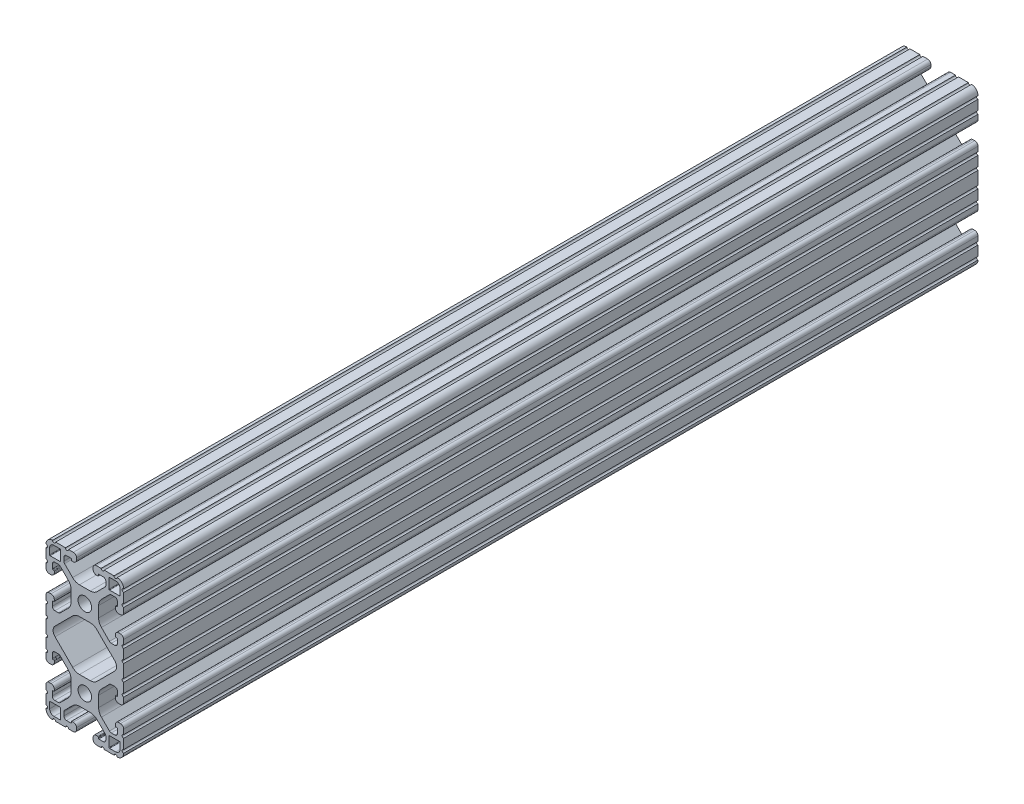
SolidWorks part; units mm, degrees
ref_plane "Front Plane" through (0, 0, 0) normal (0, 0, 1) x (1, 0, 0)
ref_plane "Top Plane" through (0, 0, 0) normal (0, 1, 0) x (1, 0, 0)
ref_plane "Right Plane" through (0, 0, 0) normal (1, 0, 0) x (0, 0, -1)
ref_plane "Plane1" through (0, 0, -914.4) normal (0, 0, -1) x (-1, 0, 0)
sketch "Sketch1" plane through (0, 0, -914.4) normal (0, 0, -1) x (-1, 0, 0)
  line L0 (19.05, -14.3256) -> (19.05, -9.4996)
  line L1 (19.05, -7.9756) -> (19.05, -5.6388)
  line L2 (17.4752, -4.064) -> (16.5608, -4.064)
  line L3 (14.986, -5.6388) -> (14.986, -6.35)
  line L4 (15.24, -6.604) -> (15.7099, -6.604)
  line L5 (15.9639, -6.858) -> (15.9639, -9.017)
  line L6 (14.6939, -10.287) -> (12.9683, -10.287)
  line L7 (12.0703, -9.915) -> (8.1476, -5.9923)
  line L8 (6.7564, -2.6337) -> (6.7564, 2.6337)
  line L9 (8.1476, 5.9923) -> (12.0703, 9.915)
  line L10 (12.9683, 10.287) -> (14.6939, 10.287)
  line L11 (15.9639, 9.017) -> (15.9639, 6.858)
  line L12 (15.7099, 6.604) -> (15.24, 6.604)
  line L13 (14.986, 6.35) -> (14.986, 5.6388)
  line L14 (16.5608, 4.064) -> (17.4752, 4.064)
  line L15 (19.05, 5.6388) -> (19.05, 7.9756)
  line L16 (19.05, 9.4996) -> (19.05, 14.3256)
  line L17 (19.05, 15.8496) -> (19.05, 22.2504)
  line L18 (19.05, 23.7744) -> (19.05, 28.6004)
  line L19 (19.05, 30.1244) -> (19.05, 32.4612)
  line L20 (17.4752, 34.036) -> (16.5608, 34.036)
  line L21 (14.986, 32.4612) -> (14.986, 31.75)
  line L22 (15.24, 31.496) -> (15.7099, 31.496)
  line L23 (15.9639, 31.242) -> (15.9639, 29.083)
  line L24 (14.6939, 27.813) -> (12.9683, 27.813)
  line L25 (12.0703, 28.185) -> (8.1476, 32.1077)
  line L26 (6.7564, 35.4663) -> (6.7564, 40.7337)
  line L27 (8.1476, 44.0923) -> (12.0703, 48.015)
  line L28 (12.9683, 48.387) -> (14.6939, 48.387)
  line L29 (15.9639, 47.117) -> (15.9639, 44.958)
  line L30 (15.7099, 44.704) -> (15.24, 44.704)
  line L31 (14.986, 44.45) -> (14.986, 43.7388)
  line L32 (16.5608, 42.164) -> (17.4752, 42.164)
  line L33 (19.05, 43.7388) -> (19.05, 46.0756)
  line L34 (19.05, 47.5996) -> (19.05, 52.4256)
  line L35 (14.3256, 57.15) -> (9.4996, 57.15)
  line L36 (7.9756, 57.15) -> (5.6388, 57.15)
  line L37 (4.064, 55.5752) -> (4.064, 54.6608)
  line L38 (5.6388, 53.086) -> (6.35, 53.086)
  line L39 (6.604, 53.34) -> (6.604, 53.8099)
  line L40 (6.858, 54.0639) -> (9.017, 54.0639)
  line L41 (10.287, 52.7939) -> (10.287, 51.0683)
  line L42 (9.915, 50.1703) -> (5.9923, 46.2476)
  line L43 (2.6337, 44.8564) -> (-2.6337, 44.8564)
  line L44 (-5.9923, 46.2476) -> (-9.915, 50.1703)
  line L45 (-10.287, 51.0683) -> (-10.287, 52.7939)
  line L46 (-9.017, 54.0639) -> (-6.858, 54.0639)
  line L47 (-6.604, 53.8099) -> (-6.604, 53.34)
  line L48 (-6.35, 53.086) -> (-5.6388, 53.086)
  line L49 (-4.064, 54.6608) -> (-4.064, 55.5752)
  line L50 (-5.6388, 57.15) -> (-7.9756, 57.15)
  line L51 (-9.4996, 57.15) -> (-14.3256, 57.15)
  line L52 (-19.05, 52.4256) -> (-19.05, 47.5996)
  line L53 (-19.05, 46.0756) -> (-19.05, 43.7388)
  line L54 (-17.4752, 42.164) -> (-16.5608, 42.164)
  line L55 (-14.986, 43.7388) -> (-14.986, 44.45)
  line L56 (-15.24, 44.704) -> (-15.7099, 44.704)
  line L57 (-15.9639, 44.958) -> (-15.9639, 47.117)
  line L58 (-14.6939, 48.387) -> (-12.9683, 48.387)
  line L59 (-12.0703, 48.015) -> (-8.1476, 44.0923)
  line L60 (-6.7564, 40.7337) -> (-6.7564, 35.4663)
  line L61 (-8.1476, 32.1077) -> (-12.0703, 28.185)
  line L62 (-12.9683, 27.813) -> (-14.6939, 27.813)
  line L63 (-15.9639, 29.083) -> (-15.9639, 31.242)
  line L64 (-15.7099, 31.496) -> (-15.24, 31.496)
  line L65 (-14.986, 31.75) -> (-14.986, 32.4612)
  line L66 (-16.5608, 34.036) -> (-17.4752, 34.036)
  line L67 (-19.05, 32.4612) -> (-19.05, 30.1244)
  line L68 (-19.05, 28.6004) -> (-19.05, 23.7744)
  line L69 (-19.05, 22.2504) -> (-19.05, 15.8496)
  line L70 (-19.05, 14.3256) -> (-19.05, 9.4996)
  line L71 (-19.05, 7.9756) -> (-19.05, 5.6388)
  line L72 (-17.4752, 4.064) -> (-16.5608, 4.064)
  line L73 (-14.986, 5.6388) -> (-14.986, 6.35)
  line L74 (-15.24, 6.604) -> (-15.7099, 6.604)
  line L75 (-15.9639, 6.858) -> (-15.9639, 9.017)
  line L76 (-14.6939, 10.287) -> (-12.9683, 10.287)
  line L77 (-12.0703, 9.915) -> (-8.1476, 5.9923)
  line L78 (-6.7564, 2.6337) -> (-6.7564, -2.6337)
  line L79 (-8.1476, -5.9923) -> (-12.0703, -9.915)
  line L80 (-12.9683, -10.287) -> (-14.6939, -10.287)
  line L81 (-15.9639, -9.017) -> (-15.9639, -6.858)
  line L82 (-15.7099, -6.604) -> (-15.24, -6.604)
  line L83 (-14.986, -6.35) -> (-14.986, -5.6388)
  line L84 (-16.5608, -4.064) -> (-17.4752, -4.064)
  line L85 (-19.05, -5.6388) -> (-19.05, -7.9756)
  line L86 (-19.05, -9.4996) -> (-19.05, -14.3256)
  line L87 (-14.3256, -19.05) -> (-9.4996, -19.05)
  line L88 (-7.9756, -19.05) -> (-5.6388, -19.05)
  line L89 (-4.064, -17.4752) -> (-4.064, -16.5608)
  line L90 (-5.6388, -14.986) -> (-6.35, -14.986)
  line L91 (-6.604, -15.24) -> (-6.604, -15.7099)
  line L92 (-6.858, -15.9639) -> (-9.017, -15.9639)
  line L93 (-10.287, -14.6939) -> (-10.287, -12.9683)
  line L94 (-9.915, -12.0703) -> (-5.9923, -8.1476)
  line L95 (-2.6337, -6.7564) -> (2.6337, -6.7564)
  line L96 (5.9923, -8.1476) -> (9.915, -12.0703)
  line L97 (10.287, -12.9683) -> (10.287, -14.6939)
  line L98 (9.017, -15.9639) -> (6.858, -15.9639)
  line L99 (6.604, -15.7099) -> (6.604, -15.24)
  line L100 (6.35, -14.986) -> (5.6388, -14.986)
  line L101 (4.064, -16.5608) -> (4.064, -17.4752)
  line L102 (5.6388, -19.05) -> (7.9756, -19.05)
  line L103 (9.4996, -19.05) -> (14.3256, -19.05)
  line L104 (-11.8872, -12.1412) -> (-11.8872, -17.018)
  line L105 (-12.1412, -17.272) -> (-15.1384, -17.272)
  line L106 (-17.272, -15.1384) -> (-17.272, -12.1412)
  line L107 (-17.018, -11.8872) -> (-12.1412, -11.8872)
  line L108 (-15.1384, 55.372) -> (-12.1412, 55.372)
  line L109 (-11.8872, 55.118) -> (-11.8872, 50.2412)
  line L110 (-12.1412, 49.9872) -> (-17.018, 49.9872)
  line L111 (-17.272, 50.2412) -> (-17.272, 53.2384)
  line L112 (5.9923, 29.9524) -> (14.6189, 21.3259)
  line L113 (14.6189, 16.7741) -> (5.9923, 8.1476)
  line L114 (2.6337, 6.7564) -> (-2.6337, 6.7564)
  line L115 (-5.9923, 8.1476) -> (-14.6189, 16.7741)
  line L116 (-14.6189, 21.3259) -> (-5.9923, 29.9524)
  line L117 (-2.6337, 31.3436) -> (2.6337, 31.3436)
  line L118 (17.272, -12.1412) -> (17.272, -15.1384)
  line L119 (15.1384, -17.272) -> (12.1412, -17.272)
  line L120 (11.8872, -17.018) -> (11.8872, -12.1412)
  line L121 (12.1412, -11.8872) -> (17.018, -11.8872)
  line L122 (12.1412, 55.372) -> (15.1384, 55.372)
  line L123 (17.272, 53.2384) -> (17.272, 50.2412)
  line L124 (17.018, 49.9872) -> (12.1412, 49.9872)
  line L125 (11.8872, 50.2412) -> (11.8872, 55.118)
  circle A0 centre (0, 0) radius 3.3274
  arc A1 (19.05, -15.8496) -> (19.05, -14.3256) centre (19.05, -15.0876) cw
  arc A2 (19.05, -9.4996) -> (19.05, -7.9756) centre (19.05, -8.7376) cw
  arc A3 (19.05, -5.6388) -> (17.4752, -4.064) centre (17.4752, -5.6388) ccw
  arc A4 (16.5608, -4.064) -> (14.986, -5.6388) centre (16.5608, -5.6388) ccw
  arc A5 (14.986, -6.35) -> (15.24, -6.604) centre (15.24, -6.35) ccw
  arc A6 (15.7099, -6.604) -> (15.9639, -6.858) centre (15.7099, -6.858) cw
  arc A7 (15.9639, -9.017) -> (14.6939, -10.287) centre (14.6939, -9.017) cw
  arc A8 (12.9683, -10.287) -> (12.0703, -9.915) centre (12.9683, -9.017) cw
  arc A9 (8.1476, -5.9923) -> (6.7564, -2.6337) centre (11.5062, -2.6337) cw
  arc A10 (6.7564, 2.6337) -> (8.1476, 5.9923) centre (11.5062, 2.6337) cw
  arc A11 (12.0703, 9.915) -> (12.9683, 10.287) centre (12.9683, 9.017) cw
  arc A12 (14.6939, 10.287) -> (15.9639, 9.017) centre (14.6939, 9.017) cw
  arc A13 (15.9639, 6.858) -> (15.7099, 6.604) centre (15.7099, 6.858) cw
  arc A14 (15.24, 6.604) -> (14.986, 6.35) centre (15.24, 6.35) ccw
  arc A15 (14.986, 5.6388) -> (16.5608, 4.064) centre (16.5608, 5.6388) ccw
  arc A16 (17.4752, 4.064) -> (19.05, 5.6388) centre (17.4752, 5.6388) ccw
  arc A17 (19.05, 7.9756) -> (19.05, 9.4996) centre (19.05, 8.7376) cw
  arc A18 (19.05, 14.3256) -> (19.05, 15.8496) centre (19.05, 15.0876) cw
  arc A19 (19.05, 22.2504) -> (19.05, 23.7744) centre (19.05, 23.0124) cw
  arc A20 (19.05, 28.6004) -> (19.05, 30.1244) centre (19.05, 29.3624) cw
  arc A21 (19.05, 32.4612) -> (17.4752, 34.036) centre (17.4752, 32.4612) ccw
  arc A22 (16.5608, 34.036) -> (14.986, 32.4612) centre (16.5608, 32.4612) ccw
  arc A23 (14.986, 31.75) -> (15.24, 31.496) centre (15.24, 31.75) ccw
  arc A24 (15.7099, 31.496) -> (15.9639, 31.242) centre (15.7099, 31.242) cw
  arc A25 (15.9639, 29.083) -> (14.6939, 27.813) centre (14.6939, 29.083) cw
  arc A26 (12.9683, 27.813) -> (12.0703, 28.185) centre (12.9683, 29.083) cw
  arc A27 (8.1476, 32.1077) -> (6.7564, 35.4663) centre (11.5062, 35.4663) cw
  arc A28 (6.7564, 40.7337) -> (8.1476, 44.0923) centre (11.5062, 40.7337) cw
  arc A29 (12.0703, 48.015) -> (12.9683, 48.387) centre (12.9683, 47.117) cw
  arc A30 (14.6939, 48.387) -> (15.9639, 47.117) centre (14.6939, 47.117) cw
  arc A31 (15.9639, 44.958) -> (15.7099, 44.704) centre (15.7099, 44.958) cw
  arc A32 (15.24, 44.704) -> (14.986, 44.45) centre (15.24, 44.45) ccw
  arc A33 (14.986, 43.7388) -> (16.5608, 42.164) centre (16.5608, 43.7388) ccw
  arc A34 (17.4752, 42.164) -> (19.05, 43.7388) centre (17.4752, 43.7388) ccw
  arc A35 (19.05, 46.0756) -> (19.05, 47.5996) centre (19.05, 46.8376) cw
  arc A36 (19.05, 52.4256) -> (19.05, 53.9496) centre (19.05, 53.1876) cw
  arc A37 (19.05, 53.9496) -> (15.8496, 57.15) centre (15.8751, 53.9751) ccw
  arc A38 (15.8496, 57.15) -> (14.3256, 57.15) centre (15.0876, 57.15) cw
  arc A39 (9.4996, 57.15) -> (7.9756, 57.15) centre (8.7376, 57.15) cw
  arc A40 (5.6388, 57.15) -> (4.064, 55.5752) centre (5.6388, 55.5752) ccw
  arc A41 (4.064, 54.6608) -> (5.6388, 53.086) centre (5.6388, 54.6608) ccw
  arc A42 (6.35, 53.086) -> (6.604, 53.34) centre (6.35, 53.34) ccw
  arc A43 (6.604, 53.8099) -> (6.858, 54.0639) centre (6.858, 53.8099) cw
  arc A44 (9.017, 54.0639) -> (10.287, 52.7939) centre (9.017, 52.7939) cw
  arc A45 (10.287, 51.0683) -> (9.915, 50.1703) centre (9.017, 51.0683) cw
  arc A46 (5.9923, 46.2476) -> (2.6337, 44.8564) centre (2.6337, 49.6062) cw
  arc A47 (-2.6337, 44.8564) -> (-5.9923, 46.2476) centre (-2.6337, 49.6062) cw
  arc A48 (-9.915, 50.1703) -> (-10.287, 51.0683) centre (-9.017, 51.0683) cw
  arc A49 (-10.287, 52.7939) -> (-9.017, 54.0639) centre (-9.017, 52.7939) cw
  arc A50 (-6.858, 54.0639) -> (-6.604, 53.8099) centre (-6.858, 53.8099) cw
  arc A51 (-6.604, 53.34) -> (-6.35, 53.086) centre (-6.35, 53.34) ccw
  arc A52 (-5.6388, 53.086) -> (-4.064, 54.6608) centre (-5.6388, 54.6608) ccw
  arc A53 (-4.064, 55.5752) -> (-5.6388, 57.15) centre (-5.6388, 55.5752) ccw
  arc A54 (-7.9756, 57.15) -> (-9.4996, 57.15) centre (-8.7376, 57.15) cw
  arc A55 (-14.3256, 57.15) -> (-15.8496, 57.15) centre (-15.0876, 57.15) cw
  arc A56 (-15.8496, 57.15) -> (-19.05, 53.9496) centre (-15.8751, 53.9751) ccw
  arc A57 (-19.05, 53.9496) -> (-19.05, 52.4256) centre (-19.05, 53.1876) cw
  arc A58 (-19.05, 47.5996) -> (-19.05, 46.0756) centre (-19.05, 46.8376) cw
  arc A59 (-19.05, 43.7388) -> (-17.4752, 42.164) centre (-17.4752, 43.7388) ccw
  arc A60 (-16.5608, 42.164) -> (-14.986, 43.7388) centre (-16.5608, 43.7388) ccw
  arc A61 (-14.986, 44.45) -> (-15.24, 44.704) centre (-15.24, 44.45) ccw
  arc A62 (-15.7099, 44.704) -> (-15.9639, 44.958) centre (-15.7099, 44.958) cw
  arc A63 (-15.9639, 47.117) -> (-14.6939, 48.387) centre (-14.6939, 47.117) cw
  arc A64 (-12.9683, 48.387) -> (-12.0703, 48.015) centre (-12.9683, 47.117) cw
  arc A65 (-8.1476, 44.0923) -> (-6.7564, 40.7337) centre (-11.5062, 40.7337) cw
  arc A66 (-6.7564, 35.4663) -> (-8.1476, 32.1077) centre (-11.5062, 35.4663) cw
  arc A67 (-12.0703, 28.185) -> (-12.9683, 27.813) centre (-12.9683, 29.083) cw
  arc A68 (-14.6939, 27.813) -> (-15.9639, 29.083) centre (-14.6939, 29.083) cw
  arc A69 (-15.9639, 31.242) -> (-15.7099, 31.496) centre (-15.7099, 31.242) cw
  arc A70 (-15.24, 31.496) -> (-14.986, 31.75) centre (-15.24, 31.75) ccw
  arc A71 (-14.986, 32.4612) -> (-16.5608, 34.036) centre (-16.5608, 32.4612) ccw
  arc A72 (-17.4752, 34.036) -> (-19.05, 32.4612) centre (-17.4752, 32.4612) ccw
  arc A73 (-19.05, 30.1244) -> (-19.05, 28.6004) centre (-19.05, 29.3624) cw
  arc A74 (-19.05, 23.7744) -> (-19.05, 22.2504) centre (-19.05, 23.0124) cw
  arc A75 (-19.05, 15.8496) -> (-19.05, 14.3256) centre (-19.05, 15.0876) cw
  arc A76 (-19.05, 9.4996) -> (-19.05, 7.9756) centre (-19.05, 8.7376) cw
  arc A77 (-19.05, 5.6388) -> (-17.4752, 4.064) centre (-17.4752, 5.6388) ccw
  arc A78 (-16.5608, 4.064) -> (-14.986, 5.6388) centre (-16.5608, 5.6388) ccw
  arc A79 (-14.986, 6.35) -> (-15.24, 6.604) centre (-15.24, 6.35) ccw
  arc A80 (-15.7099, 6.604) -> (-15.9639, 6.858) centre (-15.7099, 6.858) cw
  arc A81 (-15.9639, 9.017) -> (-14.6939, 10.287) centre (-14.6939, 9.017) cw
  arc A82 (-12.9683, 10.287) -> (-12.0703, 9.915) centre (-12.9683, 9.017) cw
  arc A83 (-8.1476, 5.9923) -> (-6.7564, 2.6337) centre (-11.5062, 2.6337) cw
  arc A84 (-6.7564, -2.6337) -> (-8.1476, -5.9923) centre (-11.5062, -2.6337) cw
  arc A85 (-12.0703, -9.915) -> (-12.9683, -10.287) centre (-12.9683, -9.017) cw
  arc A86 (-14.6939, -10.287) -> (-15.9639, -9.017) centre (-14.6939, -9.017) cw
  arc A87 (-15.9639, -6.858) -> (-15.7099, -6.604) centre (-15.7099, -6.858) cw
  arc A88 (-15.24, -6.604) -> (-14.986, -6.35) centre (-15.24, -6.35) ccw
  arc A89 (-14.986, -5.6388) -> (-16.5608, -4.064) centre (-16.5608, -5.6388) ccw
  arc A90 (-17.4752, -4.064) -> (-19.05, -5.6388) centre (-17.4752, -5.6388) ccw
  arc A91 (-19.05, -7.9756) -> (-19.05, -9.4996) centre (-19.05, -8.7376) cw
  arc A92 (-19.05, -14.3256) -> (-19.05, -15.8496) centre (-19.05, -15.0876) cw
  arc A93 (-19.05, -15.8496) -> (-15.8496, -19.05) centre (-15.8751, -15.8751) ccw
  arc A94 (-15.8496, -19.05) -> (-14.3256, -19.05) centre (-15.0876, -19.05) cw
  arc A95 (-9.4996, -19.05) -> (-7.9756, -19.05) centre (-8.7376, -19.05) cw
  arc A96 (-5.6388, -19.05) -> (-4.064, -17.4752) centre (-5.6388, -17.4752) ccw
  arc A97 (-4.064, -16.5608) -> (-5.6388, -14.986) centre (-5.6388, -16.5608) ccw
  arc A98 (-6.35, -14.986) -> (-6.604, -15.24) centre (-6.35, -15.24) ccw
  arc A99 (-6.604, -15.7099) -> (-6.858, -15.9639) centre (-6.858, -15.7099) cw
  arc A100 (-9.017, -15.9639) -> (-10.287, -14.6939) centre (-9.017, -14.6939) cw
  arc A101 (-10.287, -12.9683) -> (-9.915, -12.0703) centre (-9.017, -12.9683) cw
  arc A102 (-5.9923, -8.1476) -> (-2.6337, -6.7564) centre (-2.6337, -11.5062) cw
  arc A103 (2.6337, -6.7564) -> (5.9923, -8.1476) centre (2.6337, -11.5062) cw
  arc A104 (9.915, -12.0703) -> (10.287, -12.9683) centre (9.017, -12.9683) cw
  arc A105 (10.287, -14.6939) -> (9.017, -15.9639) centre (9.017, -14.6939) cw
  arc A106 (6.858, -15.9639) -> (6.604, -15.7099) centre (6.858, -15.7099) cw
  arc A107 (6.604, -15.24) -> (6.35, -14.986) centre (6.35, -15.24) ccw
  arc A108 (5.6388, -14.986) -> (4.064, -16.5608) centre (5.6388, -16.5608) ccw
  arc A109 (4.064, -17.4752) -> (5.6388, -19.05) centre (5.6388, -17.4752) ccw
  arc A110 (7.9756, -19.05) -> (9.4996, -19.05) centre (8.7376, -19.05) cw
  arc A111 (14.3256, -19.05) -> (15.8496, -19.05) centre (15.0876, -19.05) cw
  arc A112 (15.8496, -19.05) -> (19.05, -15.8496) centre (15.8751, -15.8751) ccw
  arc A113 (-12.1412, -11.8872) -> (-11.8872, -12.1412) centre (-12.1412, -12.1412) cw
  arc A114 (-11.8872, -17.018) -> (-12.1412, -17.272) centre (-12.1412, -17.018) cw
  arc A115 (-15.1384, -17.272) -> (-17.272, -15.1384) centre (-15.1384, -15.1384) cw
  arc A116 (-17.272, -12.1412) -> (-17.018, -11.8872) centre (-17.018, -12.1412) cw
  arc A117 (-12.1412, 55.372) -> (-11.8872, 55.118) centre (-12.1412, 55.118) cw
  arc A118 (-11.8872, 50.2412) -> (-12.1412, 49.9872) centre (-12.1412, 50.2412) cw
  arc A119 (-17.018, 49.9872) -> (-17.272, 50.2412) centre (-17.018, 50.2412) cw
  arc A120 (-17.272, 53.2384) -> (-15.1384, 55.372) centre (-15.1384, 53.2384) cw
  circle A121 centre (0, 38.1) radius 3.3274
  arc A122 (2.6337, 31.3436) -> (5.9923, 29.9524) centre (2.6337, 26.5938) cw
  arc A123 (14.6189, 21.3259) -> (14.6189, 16.7741) centre (12.343, 19.05) cw
  arc A124 (5.9923, 8.1476) -> (2.6337, 6.7564) centre (2.6337, 11.5062) cw
  arc A125 (-2.6337, 6.7564) -> (-5.9923, 8.1476) centre (-2.6337, 11.5062) cw
  arc A126 (-14.6189, 16.7741) -> (-14.6189, 21.3259) centre (-12.343, 19.05) cw
  arc A127 (-5.9923, 29.9524) -> (-2.6337, 31.3436) centre (-2.6337, 26.5938) cw
  arc A128 (17.018, -11.8872) -> (17.272, -12.1412) centre (17.018, -12.1412) cw
  arc A129 (17.272, -15.1384) -> (15.1384, -17.272) centre (15.1384, -15.1384) cw
  arc A130 (12.1412, -17.272) -> (11.8872, -17.018) centre (12.1412, -17.018) cw
  arc A131 (11.8872, -12.1412) -> (12.1412, -11.8872) centre (12.1412, -12.1412) cw
  arc A132 (15.1384, 55.372) -> (17.272, 53.2384) centre (15.1384, 53.2384) cw
  arc A133 (17.272, 50.2412) -> (17.018, 49.9872) centre (17.018, 50.2412) cw
  arc A134 (12.1412, 49.9872) -> (11.8872, 50.2412) centre (12.1412, 50.2412) cw
  arc A135 (11.8872, 55.118) -> (12.1412, 55.372) centre (12.1412, 55.118) cw
extrude "Boss-Extrude1" add sketch "Sketch1" against normal blind 419.1
equation "\"D1@Boss-Extrude1\"=(36-3)/2in"
